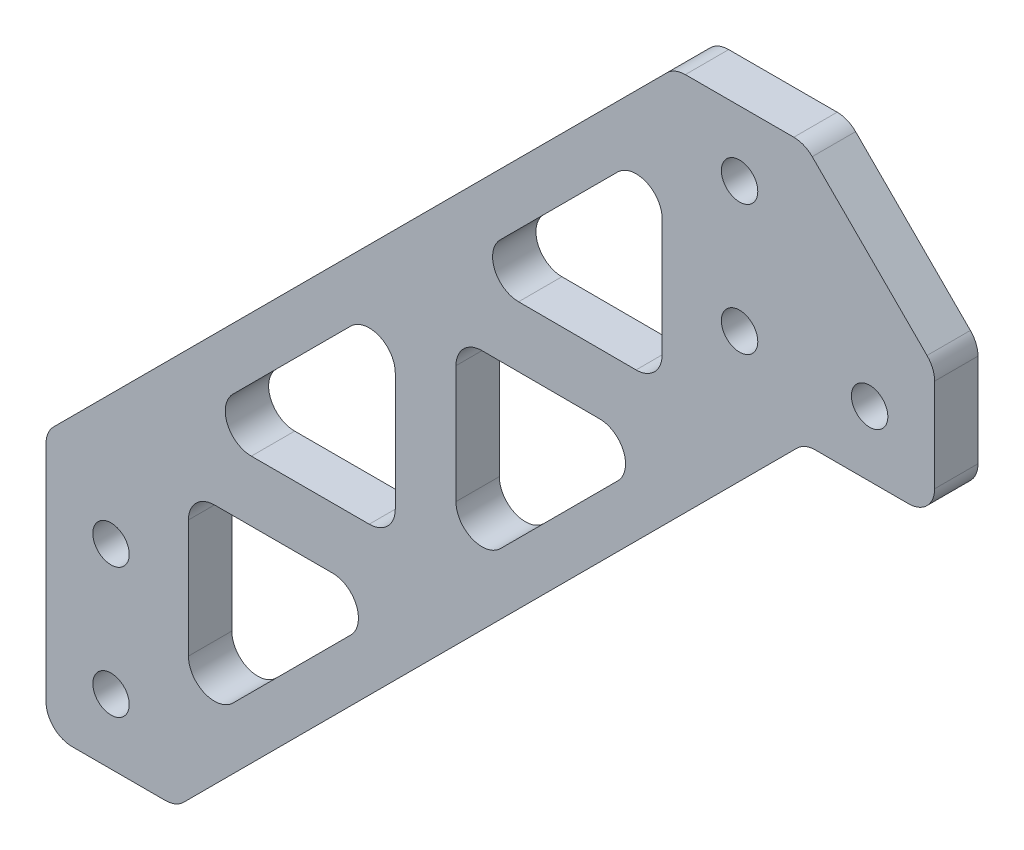
SolidWorks part; units mm, degrees
material "5052-H34"
ref_plane "正面" through (0, 0, 0) normal (0, 0, 1) x (1, 0, 0)
ref_plane "平面" through (0, 0, 0) normal (0, 1, 0) x (1, 0, 0)
ref_plane "右側面" through (0, 0, 0) normal (1, 0, 0) x (0, 0, -1)
sketch "ｽｹｯﾁ1" plane through (0, 0, 0) normal (0, 0, 1) x (1, 0, 0)
  line L0 (0, 0) -> (0, -15) construction
  line L1 (0, 0) -> (15, 0) construction
  line L2 (7.5, -22.5) -> (22.5, -7.5)
  line L3 (-7.5, -22.5) -> (7.5, -22.5)
  line L4 (-7.5, -22.5) -> (-7.5, 7.5)
  line L5 (-7.5, 7.5) -> (7.5, 7.5)
  line L6 (7.5, -22.5) -> (7.5, 7.5)
  line L7 (-7.5, -22.5) -> (7.5, 7.5) construction
  line L8 (-7.5, 7.5) -> (7.5, -22.5) construction
  line L9 (-7.5, 7.5) -> (7.5, 7.5)
  line L10 (-7.5, 7.5) -> (-7.5, -7.5)
  line L11 (-7.5, -7.5) -> (7.5, -7.5)
  line L12 (22.5, 7.5) -> (22.5, -7.5) construction
  line L13 (-7.5, 7.5) -> (22.5, -7.5) construction
  line L14 (-7.5, -7.5) -> (22.5, 7.5) construction
  line L15 (72.5, 80) -> (72.5, 50) construction
  line L16 (65, 80) -> (80, 80) construction
  line L17 (65, 80) -> (65, 50) construction
  line L18 (65, 50) -> (80, 50) construction
  line L19 (80, 80) -> (80, 50) construction
  line L20 (65, 80) -> (80, 50) construction
  line L21 (65, 50) -> (80, 80) construction
  line L22 (65, 50) -> (95, 50) construction
  line L23 (65, 50) -> (65, 65) construction
  line L24 (65, 65) -> (95, 65) construction
  line L25 (95, 50) -> (95, 65) construction
  line L26 (95, 57.5) -> (65, 57.5) construction
  line L27 (80, 50) -> (50, 50) construction
  line L28 (50, 50) -> (50, 65) construction
  line L29 (80, 65) -> (50, 65) construction
  line L30 (65, 80) -> (50, 65) construction
  line L31 (50, 65) -> (-7.5, 7.5) construction
  line L32 (7.5, 7.5) -> (22.5, 7.5) construction
  line L33 (7.5, -7.5) -> (22.5, -7.5) construction
  line L34 (-7.5, 7.5) -> (65, 80)
  line L35 (65, 80) -> (80, 80)
  line L36 (80, 80) -> (95, 65)
  line L37 (95, 65) -> (95, 50)
  line L38 (7.5, -22.5) -> (80, 50)
  line L39 (95, 50) -> (80, 50)
  circle A0 centre (0, 0) radius 2.1
  circle A1 centre (15, 0) radius 2.1 construction
  circle A2 centre (0, -15) radius 2.1
  circle A3 centre (72.5, 57.5) radius 2.1
  circle A4 centre (87.5, 57.5) radius 2.1
  circle A5 centre (72.5, 72.5) radius 2.1
  point P7 (0, -7.5)
  point P12 (7.5, 0)
  point P14 (72.5, 65)
  dimension "D1" = 4.2
  dimension "D2" = 15
  dimension "D3" = 15
  dimension "D4" = 15
  dimension "D5" = 30
  dimension "D6" = 72.5
  dimension "D7" = 42.5
extrude "ﾎﾞｽ - 押し出し1" add sketch "ｽｹｯﾁ1" along normal blind 5 contours L4 L11 L6 L5 A0 | L12 L9 L6 L11 A1 | L11 L6 L2 | L11 L4 L3 L6 A2
sketch "ｽｹｯﾁ2" plane through (0, 0, 5) normal (0, 0, 1) x (1, 0, 0)
  line L0 (67.0711, 75) -> (-2.5, 5.4289)
  line L1 (-2.5, 5.4289) -> (-2.5, -17.5)
  line L2 (-2.5, -17.5) -> (5.4289, -17.5)
  line L3 (5.4289, -17.5) -> (77.9289, 55)
  line L4 (77.9289, 55) -> (90, 55)
  line L5 (90, 55) -> (90, 62.9289)
  line L6 (90, 62.9289) -> (77.9289, 75)
  line L7 (77.9289, 75) -> (67.0711, 75)
  line L8 (-7.5, 7.5) -> (-7.5, -22.5)
  line L9 (-7.5, -22.5) -> (7.5, -22.5)
  line L10 (7.5, -22.5) -> (80, 50)
  line L11 (80, 50) -> (95, 50)
  line L12 (95, 50) -> (95, 65)
  line L13 (95, 65) -> (80, 80)
  line L14 (80, 80) -> (65, 80)
  line L15 (65, 80) -> (-7.5, 7.5)
  line L16 (-7.5, 7.5) -> (-7.5, -22.5)
  line L17 (-7.5, -22.5) -> (7.5, -22.5)
  line L18 (7.5, -22.5) -> (80, 50)
  line L19 (80, 50) -> (95, 50)
  line L20 (95, 50) -> (95, 65)
  line L21 (95, 65) -> (80, 80)
  line L22 (80, 80) -> (65, 80)
  line L23 (65, 80) -> (-7.5, 7.5)
  line L24 (5.4289, -17.5) -> (5.4289, 13.3579)
  line L25 (67.0711, 75) -> (67.0711, 44.1421)
  line L26 (5.4289, 13.3579) -> (36.2868, 13.3579)
  line L27 (36.2868, 13.3579) -> (36.2868, 44.2157)
  line L28 (36.2868, 44.2157) -> (67.0711, 44.1421)
  line L29 (8.9289, -17.5) -> (8.9289, 9.8579)
  line L30 (8.9289, 9.8579) -> (39.7868, 9.8579)
  line L31 (39.7868, 9.8579) -> (39.7868, 40.7074)
  line L32 (39.7868, 40.7074) -> (70.5711, 40.6338)
  line L33 (70.5711, 75) -> (70.5711, 40.6338)
  line L34 (1.9289, -17.5) -> (1.9289, 16.8579)
  line L35 (1.9289, 16.8579) -> (32.7868, 16.8579)
  line L36 (32.7868, 16.8579) -> (32.7868, 47.7241)
  line L37 (32.7868, 47.7241) -> (63.5711, 47.6505)
  line L38 (63.5711, 75) -> (63.5711, 47.6505)
  dimension "D1" = 0
  dimension "D2" = 5
  dimension "D3" = 3.5
  dimension "D4" = 3.5
extrude "ｶｯﾄ - 押し出し1" cut sketch "ｽｹｯﾁ2" against normal through all contours L30 L29 L3 | L35 L36 L0 | L32 L31 L3 | L38 L0 L37
fillet "ﾌｨﾚｯﾄ1" radius 3.005 12 edges at (39.7785, 47.7074, 2.5) (63.5711, 47.6505, 2.5) (63.5711, 71.5, 2.5) (63.5794, 40.6505, 2.5) (39.7868, 16.8579, 2.5) (39.7868, 40.7074, 2.5) (32.7868, 40.7157, 2.5) (8.9289, 16.8579, 2.5) (32.7868, 16.8579, 2.5) (32.7868, 9.8579, 2.5) (8.9289, 9.8579, 2.5) (8.9289, -14, 2.5)
fillet "ﾌｨﾚｯﾄ2" radius 3.005 8 edges at (80, 50, 2.5) (65, 80, 2.5) (80, 80, 2.5) (95, 65, 2.5) (95, 50, 2.5) (7.5, -22.5, 2.5) (-7.5, -22.5, 2.5) (-7.5, 7.5, 2.5)
